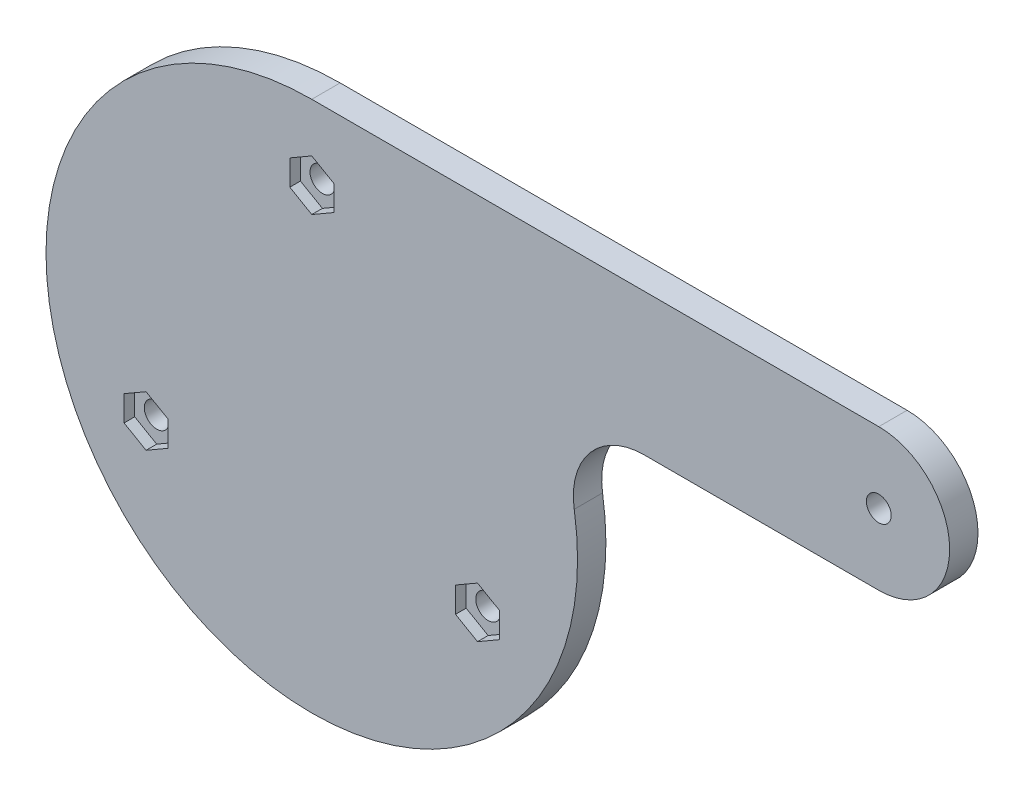
SolidWorks part; units mm, degrees
ref_plane "Front Plane" through (0, 0, 0) normal (0, 0, 1) x (1, 0, 0)
ref_plane "Top Plane" through (0, 0, 0) normal (0, 1, 0) x (1, 0, 0)
ref_plane "Right Plane" through (0, 0, 0) normal (1, 0, 0) x (0, 0, -1)
sketch "Sketch2" plane through (0, 0, 0) normal (0, 0, 1) x (1, 0, 0)
  line L0 (0, 37.5) -> (80, 37.5)
  line L5 (80, 17.5) -> (46.9042, 17.5)
  arc A0 (0, 37.5) -> (25.8372, -27.1788) centre (0, 0) ccw
  arc A3 (80, 17.5) -> (80, 37.5) centre (80, 27.5) ccw
  arc A4 (0, 37.5) -> (37.0296, 5.9211) centre (0, 0) ccw
  arc A5 (46.9042, 17.5) -> (37.0296, 5.9211) centre (46.9042, 7.5) ccw
  dimension "D1" = 75
  dimension "D2" = 80
  dimension "D3" = 20
  dimension "D4" = 10
extrude "Boss-Extrude1" add sketch "Sketch2" along normal blind 4 contours A5 L5 A3 L0 A0 A4
sketch "Sketch3" plane through (0, 0, 4) normal (0, 0, 1) x (1, 0, 0)
  line L0 (26.4831, -15.29) -> (26.4831, -11.71)
  line L1 (0, 30.58) -> (-3.1004, 28.79)
  line L2 (-3.1004, 28.79) -> (-3.1004, 25.21)
  line L3 (-3.1004, 25.21) -> (0, 23.42)
  line L4 (0, 23.42) -> (3.1004, 25.21)
  line L5 (3.1004, 25.21) -> (3.1004, 28.79)
  line L6 (3.1004, 28.79) -> (0, 30.58)
  line L7 (26.4831, -11.71) -> (23.3827, -9.92)
  line L8 (23.3827, -9.92) -> (20.2823, -11.71)
  line L9 (20.2823, -11.71) -> (20.2823, -15.29)
  line L10 (20.2823, -15.29) -> (23.3827, -17.08)
  line L11 (23.3827, -17.08) -> (26.4831, -15.29)
  line L12 (-26.4831, -15.29) -> (-23.3827, -17.08)
  line L13 (-23.3827, -17.08) -> (-20.2823, -15.29)
  line L14 (-20.2823, -15.29) -> (-20.2823, -11.71)
  line L15 (-20.2823, -11.71) -> (-23.3827, -9.92)
  line L16 (-23.3827, -9.92) -> (-26.4831, -11.71)
  line L17 (-26.4831, -11.71) -> (-26.4831, -15.29)
  circle A0 centre (0, 27) radius 3.1004 construction
  point P23 (0, 0)
  dimension "D1" = 27
  dimension "D2" = 3.58
  dimension "D3" = 3
extrude "Cut-Extrude1" cut sketch "Sketch3" against normal blind 1.5
sketch "Sketch4" plane through (0, 0, 4) normal (0, 0, 1) x (1, 0, 0)
  circle A0 centre (0, 27) radius 1.75
  circle A1 centre (23.3827, -13.5) radius 1.75
  circle A2 centre (-23.3827, -13.5) radius 1.75
  point P12 (0, 0)
  dimension "D1" = 3.5
  dimension "D2" = 3
extrude "Cut-Extrude3" cut sketch "Sketch4" against normal blind 17.5
sketch "Sketch5" plane through (0, 0, 4) normal (0, 0, 1) x (1, 0, 0)
  circle A0 centre (80, 27.5) radius 1.75
  dimension "D1" = 3.5
extrude "Cut-Extrude4" cut sketch "Sketch5" against normal blind 17.5
